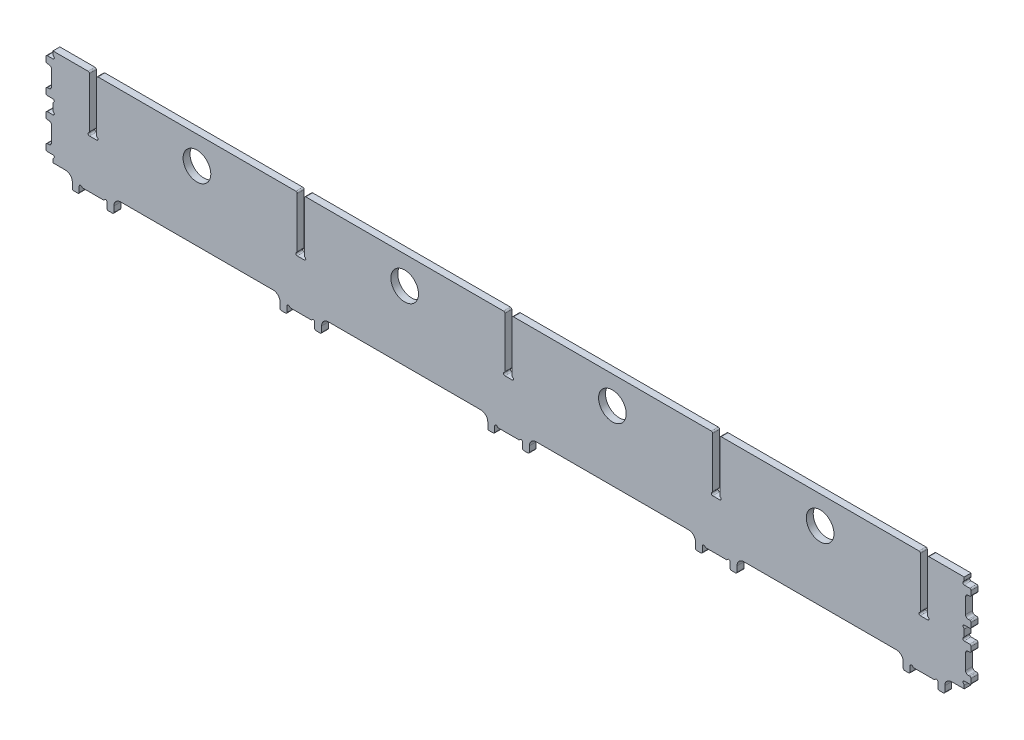
SolidWorks part; units mm, degrees
material "Plain Carbon Steel"
ref_plane "Front Plane" through (0, 0, 0) normal (0, 0, 1) x (1, 0, 0)
ref_plane "Top Plane" through (0, 0, 0) normal (0, 1, 0) x (1, 0, 0)
ref_plane "Right Plane" through (0, 0, 0) normal (1, 0, 0) x (0, 0, -1)
sketch "Sketch1" plane through (0, 0, 0) normal (0, 0, 1) x (1, 0, 0)
  line L1 (-329, 80) -> (329, 80)
  line L2 (-329, 80) -> (-329, 0)
  line L3 (-329, 0) -> (329, 0)
  line L4 (329, 80) -> (329, 0)
  point P4 (0, 0)
  dimension "D1" = 658
  dimension "D2" = 80
extrude "Boss-Extrude1" add sketch "Sketch1" along normal mid plane 5
sketch "Sketch2" plane through (0, 0, 0) normal (0, 0, 1) x (1, 0, 0)
  line L0 (-329, 0) -> (329, 0) construction
  line L1 (-15, 0) -> (-135, 0)
  line L2 (-15, 0) -> (-15, 5)
  line L3 (-20, 10) -> (-130, 10)
  line L4 (-135, 0) -> (-135, 5)
  line L5 (-165, 0) -> (-285, 0)
  line L6 (-165, 0) -> (-165, 5)
  line L7 (-170, 10) -> (-280, 10)
  line L8 (-285, 0) -> (-285, 5)
  line L9 (-315, 0) -> (-329, 0)
  line L10 (-315, 0) -> (-315, 5)
  line L11 (-320, 10) -> (-329, 10)
  line L12 (-329, 0) -> (-329, 10)
  line L13 (0, -55) -> (0, 55) construction
  line L14 (-329, 80) -> (-329, 0) construction
  arc A0 (-320, 10) -> (-315, 5) centre (-320, 5) cw
  arc A1 (-285, 5) -> (-280, 10) centre (-280, 5) cw
  arc A2 (-170, 10) -> (-165, 5) centre (-170, 5) cw
  arc A3 (-135, 5) -> (-130, 10) centre (-130, 5) cw
  arc A4 (-20, 10) -> (-15, 5) centre (-20, 5) cw
  point P16 (-285, 2.5)
  point P19 (-75, 0)
  point P30 (-135, 2.5)
  dimension "D7" = 5
  dimension "D1" = 15
  dimension "D2" = 135
  dimension "D3" = 30
  dimension "D4" = 30
  dimension "D5" = 150
  dimension "D6" = 10
extrude "Cut-Extrude1" cut sketch "Sketch2" along normal mid plane 5
mirror "Mirror1" about plane through (0, 0, 0) normal (1, 0, 0) of "Cut-Extrude1"
sketch "Sketch3" plane through (0, 0, 0) normal (0, 0, 1) x (1, 0, 0)
  line L14 (140, -5) -> (160, -5)
  line L15 (-10, -5) -> (10, -5)
  line L16 (-10, -5) -> (-10, 5)
  line L17 (-10, 5) -> (10, 5)
  line L18 (10, -5) -> (10, 5)
  line L19 (-10, -5) -> (10, 5) construction
  line L20 (-10, 5) -> (10, -5) construction
  line L21 (140, -5) -> (140, 5)
  line L22 (140, 5) -> (160, 5)
  line L23 (160, -5) -> (160, 5)
  line L24 (140, -5) -> (160, 5) construction
  line L25 (140, 5) -> (160, -5) construction
  line L26 (290, -5) -> (310, -5)
  line L27 (290, -5) -> (290, 5)
  line L28 (290, 5) -> (310, 5)
  line L29 (310, -5) -> (310, 5)
  line L30 (290, -5) -> (310, 5) construction
  line L31 (290, 5) -> (310, -5) construction
  point P14 (0, 0)
  point P21 (150, 0)
  point P26 (300, 0)
  dimension "D7" = 20
  dimension "D8" = 10
  dimension "D9" = 3
extrude "Cut-Extrude2" cut sketch "Sketch3" against normal mid plane 5
mirror "Mirror2" about plane through (0, 0, 0) normal (1, 0, 0) of "Cut-Extrude2"
sketch "Sketch4" plane through (0, 0, 0) normal (0, 0, 1) x (1, 0, 0)
  line L0 (329, 80) -> (-329, 80) construction
  line L1 (2.6, 40) -> (-2.6, 40)
  line L2 (2.6, 40) -> (2.6, 80)
  line L3 (2.6, 80) -> (-2.6, 80)
  line L4 (-2.6, 40) -> (-2.6, 80)
  line L5 (2.6, 40) -> (-2.6, 80) construction
  line L6 (2.6, 80) -> (-2.6, 40) construction
  line L7 (0, -2.75) -> (0, 2.75) construction
  point P0 (0, 60)
  dimension "D1" = 5.2
  dimension "D2" = 40
extrude "Cut-Extrude3" cut sketch "Sketch4" against normal mid plane 10
pattern_linear "LPattern1" count 3 spacing 150 along (1, 0, 0) of "Cut-Extrude3"
mirror "Mirror3" about plane through (0, 0, 0) normal (1, 0, 0) of "LPattern1"
sketch "Sketch5" plane through (329, 0, 0) normal (1, 0, 0) x (0, 0, -1)
  line L0 (-2.5, 10) -> (-2.5, 80) construction
  line L1 (-2.5, 75) -> (2.5, 75)
  line L2 (-2.5, 75) -> (-2.5, 50)
  line L3 (-2.5, 50) -> (2.5, 50)
  line L4 (2.5, 75) -> (2.5, 50)
  line L5 (2.5, 10) -> (2.5, 80) construction
  line L6 (-2.5, 80) -> (2.5, 80) construction
  line L7 (2.5, 15) -> (-2.5, 15)
  line L8 (2.5, 15) -> (2.5, 40)
  line L9 (2.5, 40) -> (-2.5, 40)
  line L10 (-2.5, 15) -> (-2.5, 40)
  line L11 (-2.5, 10) -> (2.5, 10) construction
  dimension "D1" = 5
  dimension "D2" = 25
  dimension "D3" = 5
  dimension "D4" = 25
extrude "Boss-Extrude2" add sketch "Sketch5" along normal blind 5
sketch "Sketch6" plane through (334, 0, 0) normal (1, 0, 0) x (0, 0, -1)
  line L0 (-2.5, 75) -> (-2.5, 50) construction
  line L1 (-2.5, 70) -> (2.5, 70)
  line L2 (-2.5, 70) -> (-2.5, 55)
  line L3 (-2.5, 55) -> (2.5, 55)
  line L4 (2.5, 70) -> (2.5, 55)
  line L5 (2.5, 50) -> (2.5, 75) construction
  line L6 (-2.5, 40) -> (-2.5, 15) construction
  line L7 (-2.5, 35) -> (2.5, 35)
  line L8 (-2.5, 35) -> (-2.5, 20)
  line L9 (-2.5, 20) -> (2.5, 20)
  line L10 (2.5, 35) -> (2.5, 20)
  line L11 (2.5, 15) -> (2.5, 40) construction
  line L12 (2.5, 75) -> (-2.5, 75) construction
  line L13 (-2.5, 50) -> (2.5, 50) construction
  line L14 (2.5, 40) -> (-2.5, 40) construction
  line L15 (-2.5, 15) -> (2.5, 15) construction
  dimension "D1" = 5
  dimension "D2" = 5
  dimension "D3" = 5
  dimension "D4" = 5
extrude "Cut-Extrude4" cut sketch "Sketch6" against normal blind 4
mirror "Mirror4" about plane through (0, 0, 0) normal (1, 0, 0) of "Boss-Extrude2", "Cut-Extrude4"
fillet "Fillet1" radius 2 8 edges at (-330, 20, 0) (-330, 35, 0) (-330, 55, 0) (-330, 70, 0) (330, 20, 0) (330, 35, 0) (330, 70, 0) (330, 55, 0)
sketch "Sketch7" plane through (0, 0, -2.5) normal (0, 0, -1) x (-1, 0, 0)
  line L0 (-329, 75) -> (-329, 80) construction
  line L1 (-329, 40) -> (-329, 50) construction
  line L2 (-329, 10) -> (-329, 15) construction
  line L3 (0, 2.75) -> (0, -2.75) construction
  line L4 (-334, 15) -> (-329, 15) construction
  circle A0 centre (-329, 76) radius 1
  circle A1 centre (-329, 49) radius 1
  circle A2 centre (-329, 41) radius 1
  circle A3 centre (-329, 14) radius 1
  circle A4 centre (329, 14) radius 1
  circle A5 centre (329, 41) radius 1
  circle A6 centre (329, 49) radius 1
  circle A7 centre (329, 76) radius 1
  dimension "D1" = 2
extrude "Cut-Extrude5" cut sketch "Sketch7" against normal through all
fillet "Fillet2" radius 1 24 edges at (-329, 13, 0) (-334, 15, 0) (-334, 20, 0) (-334, 35, 0) (-334, 40, 0) (-329, 42, 0) (-329, 48, 0) (-334, 50, 0) (-334, 55, 0) (-334, 70, 0) (-334, 75, 0) (-329, 77, 0) (329, 13, 0) (334, 15, 0) (334, 20, 0) (334, 35, 0) (334, 40, 0) (329, 42, 0) (329, 48, 0) (334, 50, 0) (334, 55, 0) (334, 70, 0) (334, 75, 0) (329, 77, 0)
sketch "Sketch8" plane through (0, 0, -2.5) normal (0, 0, -1) x (-1, 0, 0)
  line L0 (-302.6, 40) -> (-302.6, 80) construction
  line L1 (-297.4, 80) -> (-297.4, 40) construction
  circle A0 centre (-302.6, 41) radius 1
  circle A1 centre (-297.4, 41) radius 1
  circle A2 centre (-152.6, 41) radius 1
  circle A3 centre (-147.4, 41) radius 1
  circle A4 centre (-2.6, 41) radius 1
  circle A5 centre (2.6, 41) radius 1
  circle A6 centre (147.4, 41) radius 1
  circle A7 centre (152.6, 41) radius 1
  circle A8 centre (297.4, 41) radius 1
  circle A9 centre (302.6, 41) radius 1
  dimension "D1" = 2
extrude "Cut-Extrude6" cut sketch "Sketch8" against normal through all
fillet "Fillet3" radius 1 20 edges at (302.6, 80, 0) (297.4, 80, 0) (147.4, 80, 0) (152.6, 80, 0) (-2.6, 80, 0) (2.6, 80, 0) (-152.6, 80, 0) (-147.4, 80, 0) (-297.4, 80, 0) (-302.6, 80, 0) (-302.6, 42, 0) (-297.4, 42, 0) (-152.6, 42, 0) (-147.4, 42, 0) (2.6, 42, 0) (-2.6, 42, 0) (147.4, 42, 0) (152.6, 42, 0) (302.6, 42, 0) (297.4, 42, 0)
sketch "Sketch9" plane through (0, 0, -2.5) normal (0, 0, -1) x (-1, 0, 0)
  line L0 (-310, 5) -> (-290, 5) construction
  circle A0 centre (-309, 5) radius 1
  circle A1 centre (-291, 5) radius 1
  circle A2 centre (-159, 5) radius 1
  circle A3 centre (-141, 5) radius 1
  circle A4 centre (-9, 5) radius 1
  circle A5 centre (9, 5) radius 1
  circle A6 centre (141, 5) radius 1
  circle A7 centre (159, 5) radius 1
  circle A8 centre (291, 5) radius 1
  circle A9 centre (309, 5) radius 1
  dimension "D1" = 2
extrude "Cut-Extrude7" cut sketch "Sketch9" against normal through all
fillet "Fillet4" radius 1 30 edges at (-315, 0, 0) (-310, 0, 0) (-308, 5, 0) (-292, 5, 0) (-290, 0, 0) (-285, 0, 0) (-165, 0, 0) (-160, 0, 0) (-158, 5, 0) (-142, 5, 0) (-140, 0, 0) (-135, 0, 0) (-15, 0, 0) (-10, 0, 0) (-8, 5, 0) (8, 5, 0) (10, 0, 0) (15, 0, 0) (135, 0, 0) (140, 0, 0) (142, 5, 0) (158, 5, 0) (160, 0, 0) (165, 0, 0) (285, 0, 0) (290, 0, 0) (292, 5, 0) (308, 5, 0) (310, 0, 0) (315, 0, 0)
sketch "Sketch10" plane through (0, 0, -2.5) normal (0, 0, -1) x (-1, 0, 0)
  line L0 (-146.4, 80) -> (-3.6, 80) construction
  line L1 (0, 2.75) -> (0, -2.75) construction
  circle A0 centre (-75, 60) radius 10
  circle A1 centre (-225, 60) radius 10
  circle A2 centre (225, 60) radius 10
  circle A3 centre (75, 60) radius 10
  dimension "D1" = 20
  dimension "D2" = 20
  dimension "D3" = 75
extrude "Cut-Extrude8" cut sketch "Sketch10" against normal through all
